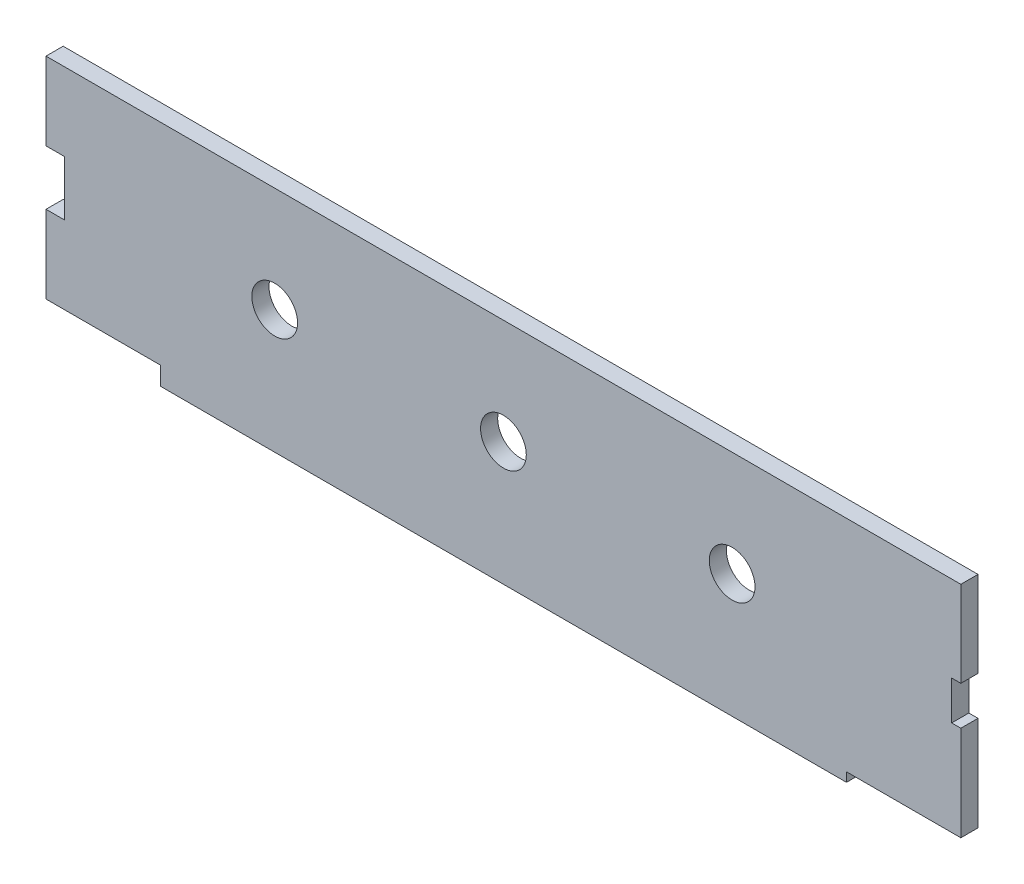
SolidWorks part; units mm, degrees
ref_plane "Alzado" through (0, 0, 0) normal (0, 0, 1) x (1, 0, 0)
ref_plane "Planta" through (0, 0, 0) normal (0, 1, 0) x (1, 0, 0)
ref_plane "Vista lateral" through (0, 0, 0) normal (1, 0, 0) x (0, 0, -1)
sketch "Croquis1" plane through (0, 0, 0) normal (0, 0, 1) x (1, 0, 0)
  line L0 (-40, 9.2) -> (40, 9.2)
  line L1 (40, 9.2) -> (40, 1.7)
  line L2 (40, 1.7) -> (39.2, 1.7)
  line L3 (39.2, 1.7) -> (39.2, -1.7)
  line L4 (39.2, -1.7) -> (40, -1.7)
  line L5 (40, -1.7) -> (40, -10)
  line L6 (40, -10) -> (30, -10)
  line L7 (30, -10) -> (30, -10.8)
  line L8 (30, -10.8) -> (-30, -10.8)
  line L9 (-30, -10.8) -> (-30, -9.2)
  line L10 (-30, -9.2) -> (-40, -9.2)
  line L11 (-40, -9.2) -> (-40, -2.4)
  line L12 (-40, -2.4) -> (-38.4, -2.4)
  line L13 (-38.4, -2.4) -> (-38.4, 2.4)
  line L14 (-38.4, 2.4) -> (-40, 2.4)
  line L15 (-40, 2.4) -> (-40, 9.2)
  line L16 (39.2, 0) -> (-38.4, 0) construction
  circle A0 centre (20, 0) radius 2
  circle A1 centre (0, 0) radius 2
  circle A2 centre (-20, 0) radius 2
  point P16 (-38.4, 0)
  point P18 (39.2, 0)
  point P19 (0, 9.2)
  dimension "D9" = 4
  dimension "D10" = 20
  dimension "D11" = 20
  dimension "D12" = 20
  dimension "D1" = 80
  dimension "D2" = 10
  dimension "D3" = 10
  dimension "D4" = 20
  dimension "D5" = 4.8
  dimension "D6" = 3.4
  dimension "D7" = 1.6
  dimension "D8" = 0.8
extrude "Saliente-Extruir1" add sketch "Croquis1" along normal blind 1.5
